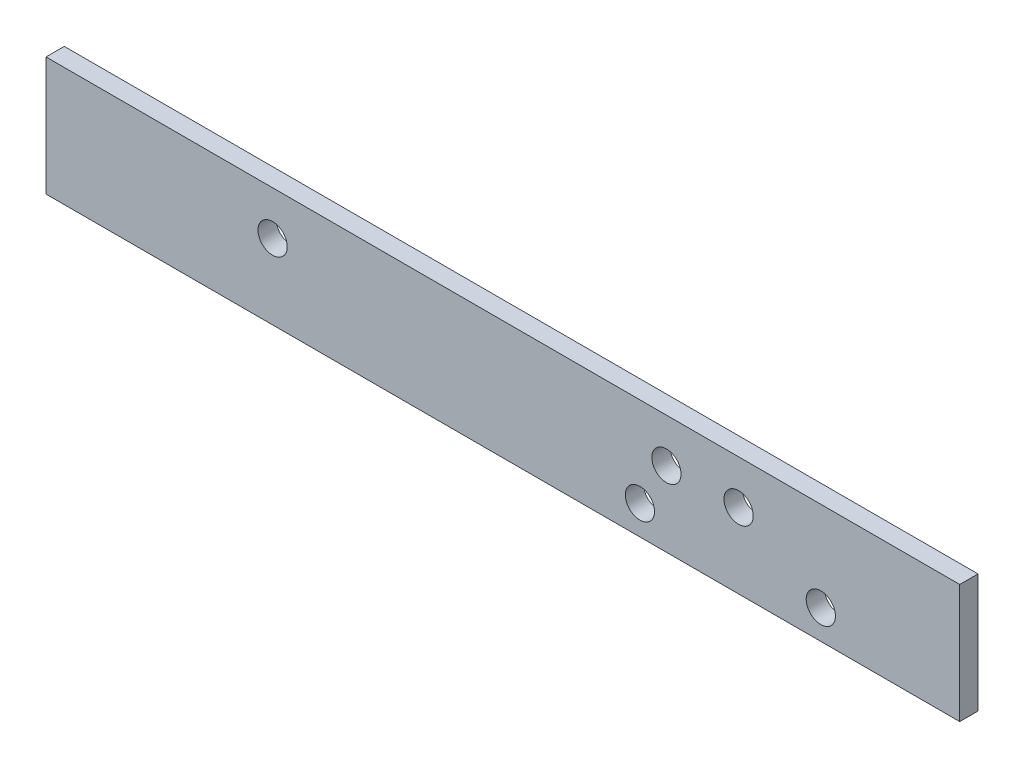
SolidWorks part; units mm, degrees
ref_plane "Front Plane" through (0, 0, 0) normal (0, 0, 1) x (1, 0, 0)
ref_plane "Top Plane" through (0, 0, 0) normal (0, 1, 0) x (1, 0, 0)
ref_plane "Right Plane" through (0, 0, 0) normal (1, 0, 0) x (0, 0, -1)
sketch "Sketch1" plane through (0, 0, 0) normal (0, 0, 1) x (1, 0, 0)
  line L0 (100, 6.5) -> (0, 6.5) construction
  line L1 (0, 0) -> (100, 0)
  line L2 (0, 0) -> (0, 13)
  line L3 (0, 13) -> (100, 13)
  line L4 (100, 0) -> (100, 13)
  line L5 (50, 13) -> (50, 0) construction
  circle A0 centre (84.8, 3.2) radius 1.6
  circle A1 centre (75.8, 8.2) radius 1.6
  circle A2 centre (67.9, 8.2) radius 1.6
  circle A3 centre (65, 3.2) radius 1.6
  circle A8 centre (24.8, 8.2) radius 1.6
  point P17 (0, 0)
  dimension "D3" = 3.2
  dimension "D1" = 100
  dimension "D2" = 13
  dimension "D4" = 15.2
  dimension "D5" = 3.2
  dimension "D6" = 9
  dimension "D7" = 7.9
  dimension "D8" = 19.8
  dimension "D9" = 5
  dimension "D10" = 51
extrude "Boss-Extrude1" add sketch "Sketch1" along normal blind 2
